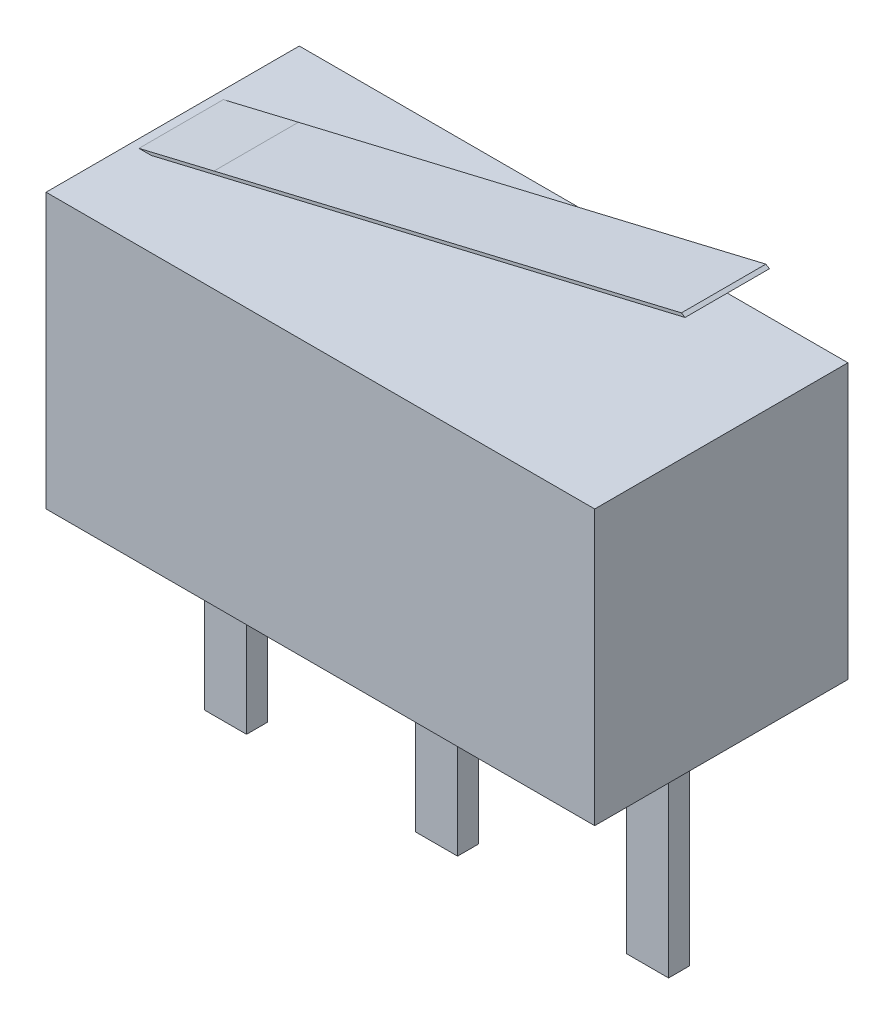
SolidWorks part; units mm, degrees
ref_plane "Plan de face" through (0, 0, 0) normal (0, 0, 1) x (1, 0, 0)
ref_plane "Plan de dessus" through (0, 0, 0) normal (0, 1, 0) x (1, 0, 0)
ref_plane "Plan de droite" through (0, 0, 0) normal (1, 0, 0) x (0, 0, -1)
sketch "Esquisse1" plane through (0, 0, 0) normal (0, 1, 0) x (1, 0, 0)
  line L1 (-6.5, -3) -> (6.5, -3)
  line L2 (-6.5, -3) -> (-6.5, 3)
  line L3 (-6.5, 3) -> (6.5, 3)
  line L4 (6.5, -3) -> (6.5, 3)
  line L5 (-6.5, -3) -> (6.5, 3) construction
  line L6 (-6.5, 3) -> (6.5, -3) construction
  point P0 (0, 0)
  dimension "D1" = 13
  dimension "D2" = 6
extrude "Boss.-Extru.1" add sketch "Esquisse1" along normal blind 6.5
sketch "Esquisse2" plane through (0, 0, 0) normal (0, -1, 0) x (1, 0, 0)
  line L0 (-6.5, 0) -> (6.5, 0) construction
  line L1 (-6.5, -3) -> (-6.5, 3) construction
  line L2 (6.5, 3) -> (6.5, -3) construction
  line L4 (-4.5, -0.25) -> (-5.5, -0.25)
  line L5 (-4.5, -0.25) -> (-4.5, 0.25)
  line L6 (-4.5, 0.25) -> (-5.5, 0.25)
  line L7 (-5.5, -0.25) -> (-5.5, 0.25)
  line L8 (-4.5, -0.25) -> (-5.5, 0.25) construction
  line L9 (-4.5, 0.25) -> (-5.5, -0.25) construction
  line L10 (0.5, -0.25) -> (-0.5, -0.25)
  line L11 (0.5, -0.25) -> (0.5, 0.25)
  line L12 (0.5, 0.25) -> (-0.5, 0.25)
  line L13 (-0.5, -0.25) -> (-0.5, 0.25)
  line L14 (0.5, -0.25) -> (-0.5, 0.25) construction
  line L15 (0.5, 0.25) -> (-0.5, -0.25) construction
  line L16 (5.5, -0.25) -> (4.5, -0.25)
  line L17 (5.5, -0.25) -> (5.5, 0.25)
  line L18 (5.5, 0.25) -> (4.5, 0.25)
  line L19 (4.5, -0.25) -> (4.5, 0.25)
  line L20 (5.5, -0.25) -> (4.5, 0.25) construction
  line L21 (5.5, 0.25) -> (4.5, -0.25) construction
  point P6 (-5, 0)
  point P11 (0, 0)
  point P16 (5, 0)
  dimension "D1" = 1
  dimension "D2" = 1
  dimension "D3" = 1
  dimension "D4" = 1
  dimension "D5" = 1
  dimension "D6" = 6
  dimension "D7" = 0.5
  dimension "D8" = 0.5
  dimension "D9" = 0.5
extrude "Boss.-Extru.2" add sketch "Esquisse2" along normal blind 5
ref_plane "Plan1" through (0, 0, 0) normal (0, 0, 1) x (1, 0, 0)
sketch "Esquisse3" plane through (0, 0, 0) normal (0, 0, 1) x (1, 0, 0)
  line L1 (-6.0081, 6.5) -> (6.641, 9.5)
  line L2 (-6.5, 6.5) -> (6.5, 6.5) construction
  line L3 (6.641, 9.5) -> (6.5554, 9.5518)
  line L4 (6.5554, 9.5518) -> (-4.5207, 6.9249)
  line L5 (-4.5207, 6.9249) -> (-6.3, 6.5)
  line L6 (-6.3, 6.5) -> (-6.0081, 6.5)
  dimension "D2" = 3
  dimension "D1" = 0.2
  dimension "D3" = 0.1
  dimension "D4" = 13
extrude "Boss.-Extru.3" add sketch "Esquisse3" along normal mid plane 2
